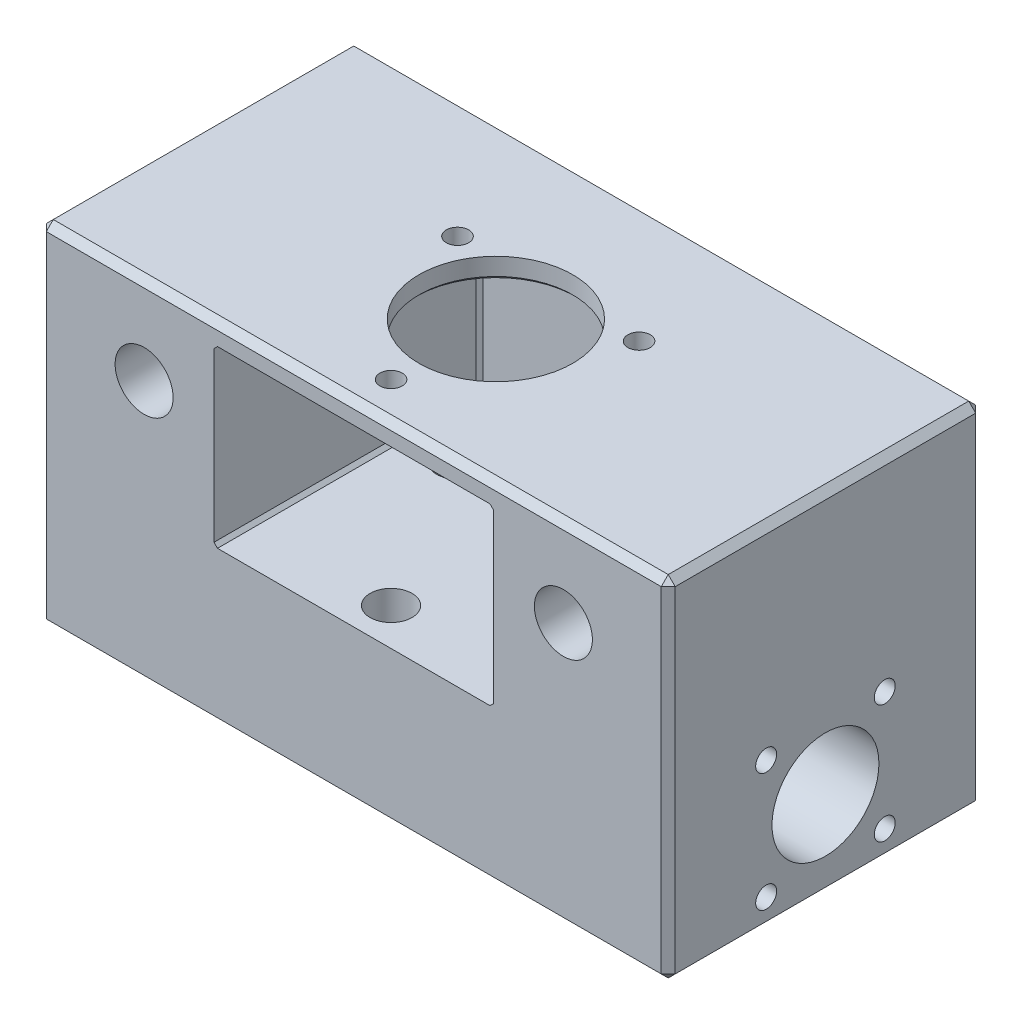
SolidWorks part; units mm, degrees
ref_plane "前视基准面" through (0, 0, 0) normal (0, 0, 1) x (1, 0, 0)
ref_plane "上视基准面" through (0, 0, 0) normal (0, 1, 0) x (1, 0, 0)
ref_plane "右视基准面" through (0, 0, 0) normal (1, 0, 0) x (0, 0, -1)
sketch "Sketch1" plane through (0, 0, 0) normal (0, 1, 0) x (1, 0, 0)
  line L1 (-45, 22.5) -> (45, 22.5)
  line L2 (-45, 22.5) -> (-45, -22.5)
  line L3 (-45, -22.5) -> (45, -22.5)
  line L4 (45, 22.5) -> (45, -22.5)
  line L5 (-45, 22.5) -> (45, -22.5) construction
  line L6 (-45, -22.5) -> (45, 22.5) construction
  point P0 (0, 0)
  dimension "D1" = 90
  dimension "D2" = 45
extrude "Boss-Extrude1" add sketch "Sketch1" along normal blind 50
sketch "Sketch2" plane through (0, 0, 22.5) normal (0, 0, 1) x (1, 0, 0)
  line L0 (-45, 25) -> (45, 25) construction
  line L1 (-45, 50) -> (-45, 0) construction
  line L2 (45, 50) -> (45, 0) construction
  line L3 (-45, 50) -> (45, 50) construction
  line L4 (0, -6.1777) -> (0, 0) construction
  circle A0 centre (-30, 37.5) radius 4.15
  circle A1 centre (30, 37.5) radius 4.15
  dimension "D1" = 8.3
  dimension "D2" = 30
  dimension "D3" = 12.5
extrude "Cut-Extrude1" cut sketch "Sketch2" against normal blind 28.2967
sketch "Sketch3" plane through (45, 0, 0) normal (1, 0, 0) x (0, 0, -1)
  line L0 (-22.5, 0) -> (22.5, 0) construction
  circle A0 centre (0, 12.5) radius 7.65
  dimension "D1" = 12.5
  dimension "D2" = 15.3
extrude "Cut-Extrude2" cut sketch "Sketch3" against normal through all
sketch "Sketch4" plane through (45, 0, 0) normal (1, 0, 0) x (0, 0, -1)
  line L0 (0, 12.5) -> (-8.4853, 20.9853) construction
  line L1 (0, 12.5) -> (-12, 12.5) construction
  circle A0 centre (0, 12.5) radius 12 construction
  circle A1 centre (-8.4853, 20.9853) radius 1.5
  circle A2 centre (8.4853, 20.9853) radius 1.5
  circle A3 centre (8.4853, 4.0147) radius 1.5
  circle A4 centre (-8.4853, 4.0147) radius 1.5
  point P15 (0, 12.5)
  dimension "D1" = 24
  dimension "D3" = 3
  dimension "D4" = 4
  dimension "D2" = 45
extrude "Cut-Extrude3" cut sketch "Sketch4" against normal blind 10
mirror "Mirror1" about plane through (0, 0, 0) normal (1, 0, 0) of "Cut-Extrude3"
chamfer "Chamfer1" distance 1 angle 45 12 edges at (-45, 0, 0) (45, 0, 0) (45, 25, -22.5) (0, 0, -22.5) (-45, 25, -22.5) (0, 50, 22.5) (-45, 50, 0) (0, 50, -22.5) (45, 50, 0) (45, 25, 22.5) (0, 0, 22.5) (-45, 25, 22.5)
sketch "Sketch6" plane through (0, 0, 22.5) normal (0, 0, 1) x (1, 0, 0)
  line L0 (-44, 50) -> (44, 50) construction
  line L1 (-20, 22) -> (20, 22)
  line L2 (-20, 22) -> (-20, 47)
  line L3 (-20, 47) -> (20, 47)
  line L4 (20, 22) -> (20, 47)
  line L5 (-20, 22) -> (20, 47) construction
  line L6 (-20, 47) -> (20, 22) construction
  point P0 (0, 34.5)
  point P8 (0, 0)
  dimension "D1" = 3
  dimension "D2" = 25
  dimension "D3" = 40
extrude "Cut-Extrude5" cut sketch "Sketch6" against normal blind 38
sketch "Sketch5" plane through (0, 50, 0) normal (0, 1, 0) x (1, 0, 0)
  circle A0 centre (0, -2.1648) radius 15 construction
  circle A1 centre (0, -2.1648) radius 19.3352 construction
  circle A2 centre (0, -17.1648) radius 1.6
  circle A3 centre (-12.9904, 5.3352) radius 1.6
  circle A4 centre (12.9904, 5.3352) radius 1.6
  circle A5 centre (0, -2.1648) radius 11
  point P12 (0, -2.1648)
  dimension "D1" = 30
  dimension "D2" = 3.2
  dimension "D4" = 22
  dimension "D3" = 2.1648
extrude "Cut-Extrude4" cut sketch "Sketch5" against normal up to next
sketch "Sketch8" plane through (0, 0, 0) normal (0, -1, 0) x (1, 0, 0)
  circle A0 centre (0, 17.1648) radius 3
  circle A1 centre (0, 2.1648) radius 11 construction
  circle A2 centre (0, 2.1648) radius 11 construction
  circle A3 centre (12.9904, -5.3352) radius 3
  circle A4 centre (0, 2.1648) radius 11 construction
  circle A5 centre (-12.9904, -5.3352) radius 3
  circle A6 centre (0, 2.1648) radius 11 construction
  point P15 (0, 2.1648)
  dimension "D1" = 6
extrude "Cut-Extrude6" cut sketch "Sketch8" against normal up to next
chamfer "Chamfer2" distance 0.5 angle 45 9 edges at (0, 47, 13.1648) (20, 34.5, -15.5) (20, 47, 3.5) (0, 47, -15.5) (-20, 47, 3.5) (-20, 34.5, -15.5) (20, 22, 3.5) (-20, 22, 3.5) (0, 22, -15.5)
